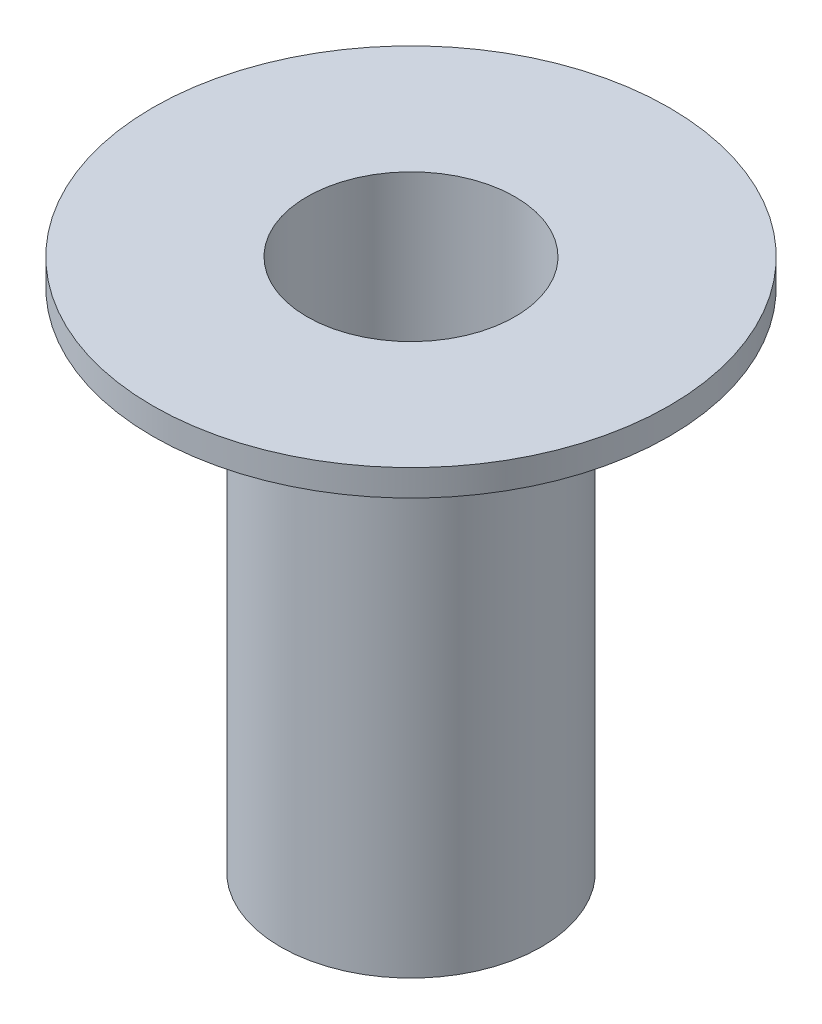
SolidWorks part; units mm, degrees
ref_plane "Front Plane" through (0, 0, 0) normal (0, 0, 1) x (1, 0, 0)
ref_plane "Top Plane" through (0, 0, 0) normal (0, 1, 0) x (1, 0, 0)
ref_plane "Right Plane" through (0, 0, 0) normal (1, 0, 0) x (0, 0, -1)
sketch "Sketch1" plane through (0, 0, 0) normal (0, 1, 0) x (1, 0, 0)
  circle A0 centre (0, 0) radius 1.5
  circle A1 centre (0, 0) radius 1.881
  dimension "D1" = 0.381
extrude "Boss-Extrude1" add sketch "Sketch1" along normal blind 7.3
sketch "Sketch2" plane through (0, 7.3, 0) normal (0, 1, 0) x (-1, 0, 0)
  circle A0 centre (0, 0) radius 1.5
  circle A1 centre (0, 0) radius 3.725
extrude "Boss-Extrude2" add sketch "Sketch2" along normal blind 0.381
